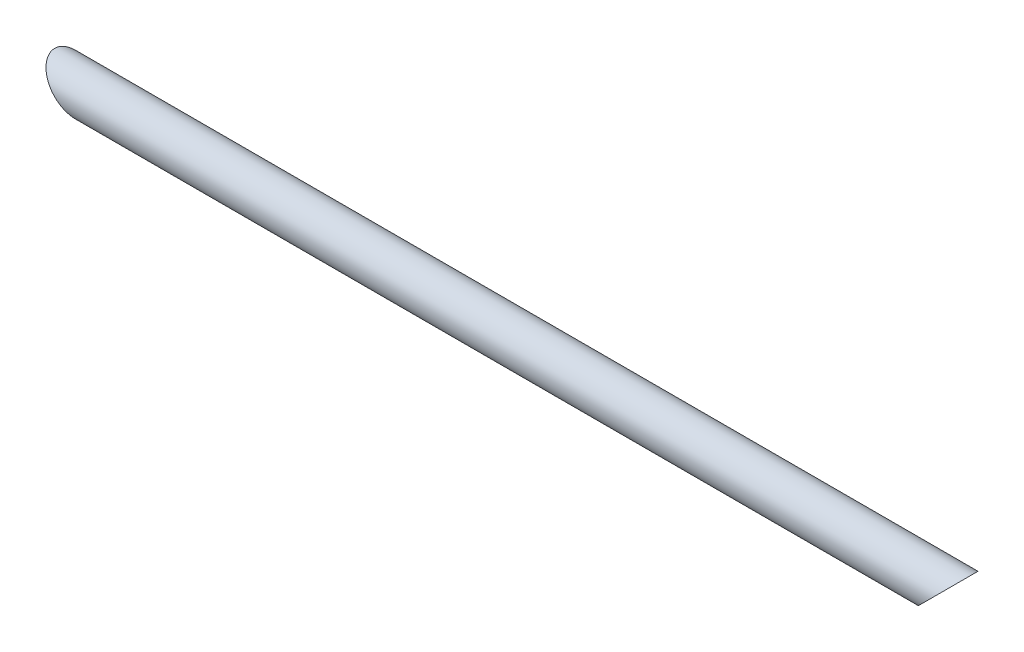
SolidWorks part; units mm, degrees
ref_plane "Front Plane" through (0, 0, 0) normal (0, 0, 1) x (1, 0, 0)
ref_plane "Top Plane" through (0, 0, 0) normal (0, 1, 0) x (1, 0, 0)
ref_plane "Right Plane" through (0, 0, 0) normal (1, 0, 0) x (0, 0, -1)
sketch "Sketch1" plane through (0, 0, 0) normal (1, 0, 0) x (0, 0, -1)
  circle A0 centre (0, 0) radius 12.7
  dimension "D1" = 25.4
extrude "Extrude-Thin1" add sketch "Sketch1" along normal mid plane 550.8 thin thin type one direction reverse wall 1
sketch "Sketch2" plane through (0, 0, 0) normal (0, 0, 1) x (1, 0, 0)
  line L0 (275.4, 12.7) -> (250, -12.7) construction
  line L1 (-275.4, -12.7) -> (275.4, -12.7) construction
  line L2 (275.4, 12.7) -> (-275.4, 12.7) construction
  line L3 (0, -55) -> (0, 55) construction
  line L4 (-275.4, 12.7) -> (-250, -12.7) construction
  dimension "D1" = 45
ref_plane "Plane1" through (131.35, -131.35, 0) normal (-0.7071, 0.7071, 0) x (-0.7071, -0.7071, 0)
other "SurfaceCut1"
sketch "Sketch3" plane through (0, 0, 0) normal (0, 0, 1) x (1, 0, 0)
  line L0 (-275.4, 12.7) -> (-250, -12.7) construction
  line L1 (-275.4, -12.7) -> (250, -12.7) construction
  line L2 (275.4, 12.7) -> (-275.4, 12.7) construction
  dimension "D1" = 45
ref_plane "Plane2" through (-131.35, -131.35, 0) normal (-0.7071, -0.7071, 0) x (0.7071, -0.7071, 0)
other "SurfaceCut2"
